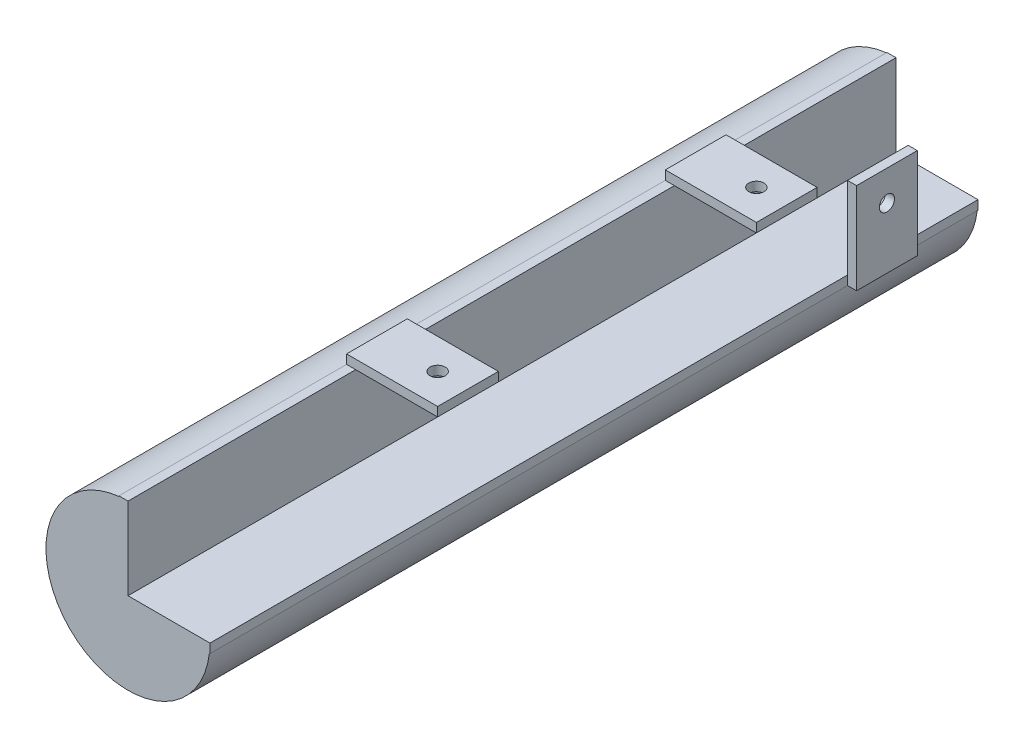
SolidWorks part; units mm, degrees
ref_plane "Front Plane" through (0, 0, 0) normal (0, 0, 1) x (1, 0, 0)
ref_plane "Top Plane" through (0, 0, 0) normal (0, 1, 0) x (1, 0, 0)
ref_plane "Right Plane" through (0, 0, 0) normal (1, 0, 0) x (0, 0, -1)
sketch "Sketch4" plane through (0, 0, 0) normal (0, 0, 1) x (1, 0, 0)
  line L0 (0, 0) -> (27, 0)
  line L5 (0, 27) -> (0, 0)
  line L6 (0, 27) -> (-3, 27)
  line L7 (-3, 27) -> (-3, 26.8328)
  line L8 (27, 0) -> (27, -3)
  line L9 (27, -3) -> (26.8001, -3)
  arc A1 (-3, 26.8328) -> (26.8001, -3) centre (-0.0331, -0.0037) ccw
  dimension "D3" = 27
  dimension "D1" = 27
  dimension "D2" = 27
  dimension "D4" = 3
  dimension "D5" = 3
  dimension "D6" = 0.1672
  dimension "D7" = 0.1999
extrude "Boss-Extrude1" add sketch "Sketch4" along normal mid plane 253
sketch "Sketch12" plane through (27, 0, 0) normal (1, 0, 0) x (0, 0, -1)
  line L0 (-126.5, -3) -> (126.5, -3) construction
  line L1 (83.5, -3) -> (103.5, -3)
  line L2 (83.5, -3) -> (83.5, 27)
  line L3 (83.5, 27) -> (103.5, 27)
  line L4 (103.5, -3) -> (103.5, 27)
  line L5 (-126.5, 0) -> (-126.5, 27) construction
  dimension "D1" = 20
  dimension "D2" = 30
  dimension "D3" = 210
extrude "Boss-Extrude6" add sketch "Sketch12" along normal blind 3
sketch "Sketch13" plane through (30, 0, 0) normal (1, 0, 0) x (0, 0, -1)
  line L0 (103.5, 27) -> (83.5, 27) construction
  line L1 (83.5, 27) -> (83.5, -3) construction
  circle A0 centre (93.5, 17) radius 2.5
  dimension "D1" = 5
  dimension "D2" = 10
  dimension "D3" = 10
extrude "Cut-Extrude3" cut sketch "Sketch13" against normal up to next
sketch "Sketch17" plane through (0, 27, 0) normal (0, 1, 0) x (1, 0, 0)
  line L0 (-3, -126.5) -> (-3, 126.5) construction
  line L1 (-3, 73.5) -> (27, 73.5)
  line L2 (-3, 73.5) -> (-3, 53.5)
  line L3 (-3, 53.5) -> (27, 53.5)
  line L4 (27, 73.5) -> (27, 53.5)
  line L5 (27, -126.5) -> (27, 83.5) construction
  line L7 (-3, -51.5) -> (27, -51.5)
  line L8 (-3, -51.5) -> (-3, -31.5)
  line L9 (-3, -31.5) -> (27, -31.5)
  line L10 (27, -51.5) -> (27, -31.5)
  line L11 (27, -126.5) -> (0, -126.5) construction
  dimension "D1" = 75
  dimension "D2" = 20
  dimension "D3" = 20
  dimension "D4" = 180
extrude "Boss-Extrude10" add sketch "Sketch17" along normal blind 3
sketch "Sketch18" plane through (0, 30, 0) normal (0, 1, 0) x (1, 0, 0)
  line L0 (27, 53.5) -> (27, 73.5) construction
  line L1 (27, 73.5) -> (-3, 73.5) construction
  line L2 (27, -51.5) -> (27, -31.5) construction
  line L3 (27, -31.5) -> (-3, -31.5) construction
  circle A0 centre (17, 63.5) radius 2.5
  circle A1 centre (17, -41.5) radius 2.5
  dimension "D1" = 5
  dimension "D2" = 5
  dimension "D3" = 10
  dimension "D4" = 10
  dimension "D5" = 10
  dimension "D6" = 10
extrude "Cut-Extrude5" cut sketch "Sketch18" against normal up to next
